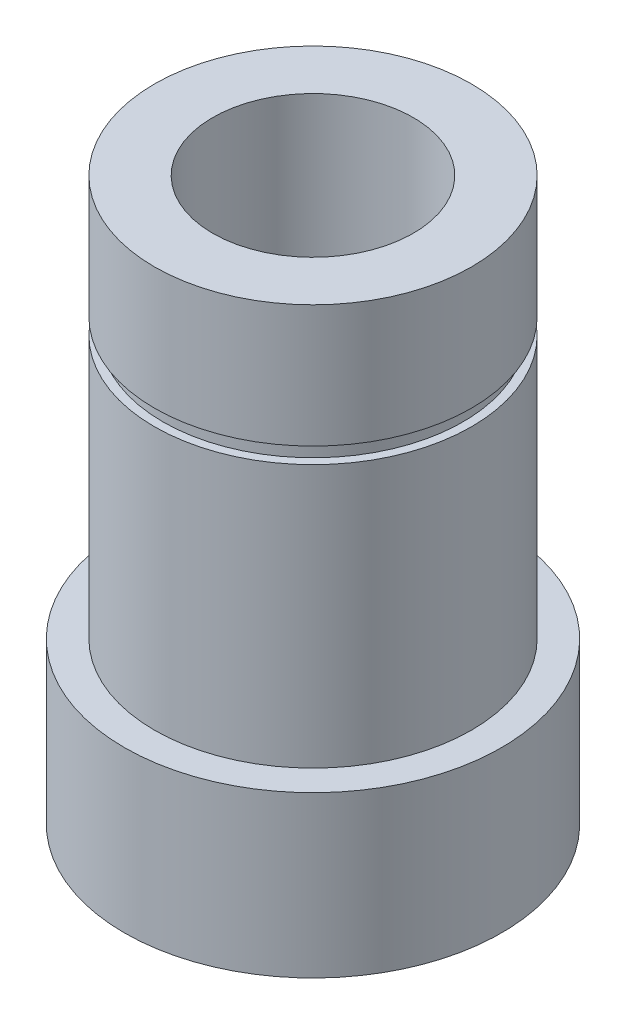
SolidWorks part; units mm, degrees
material "Plain Carbon Steel"
ref_plane "Front Plane" through (0, 0, 0) normal (0, 0, 1) x (1, 0, 0)
ref_plane "Top Plane" through (0, 0, 0) normal (0, 1, 0) x (1, 0, 0)
ref_plane "Right Plane" through (0, 0, 0) normal (1, 0, 0) x (0, 0, -1)
sketch "Sketch1" plane through (0, 0, 0) normal (0, 1, 0) x (1, 0, 0)
  circle A0 centre (0, 0) radius 4.7
  dimension "D1" = 9.4
extrude "Boss-Extrude1" add sketch "Sketch1" along normal blind 4
sketch "Sketch2" plane through (0, 4, 0) normal (0, 1, 0) x (1, 0, 0)
  circle A0 centre (0, 0) radius 3.95
  dimension "D1" = 7.9
extrude "Boss-Extrude2" add sketch "Sketch2" along normal blind 6.5
sketch "Sketch3" plane through (0, 10.5, 0) normal (0, 1, 0) x (1, 0, 0)
  circle A0 centre (0, 0) radius 3.95
  dimension "D1" = 7.9
extrude "Boss-Extrude3" add sketch "Sketch3" along normal blind 1
sketch "Sketch4" plane through (0, 11.5, 0) normal (0, 1, 0) x (1, 0, 0)
  circle A0 centre (0, 0) radius 3.95
  dimension "D1" = 7.9
extrude "Boss-Extrude4" add sketch "Sketch4" along normal blind 2.5
sketch "Sketch5" plane through (0, 14, 0) normal (0, 1, 0) x (1, 0, 0)
  circle A0 centre (0, 0) radius 2.5
  dimension "D1" = 5
extrude "Cut-Extrude1" cut sketch "Sketch5" against normal through all
ref_plane "基准面1" through (0, 10.75, 0) normal (0, 1, 0) x (1, 0, 0)
sketch "草图1" plane through (0, 10.75, 0) normal (0, 1, 0) x (1, 0, 0)
  circle A0 centre (0, 0) radius 3.74
  dimension "D1" = 7.48
extrude "切除-拉伸1" cut sketch "草图1" against normal blind 0.2 and the other way blind 0.2 flip side to cut
